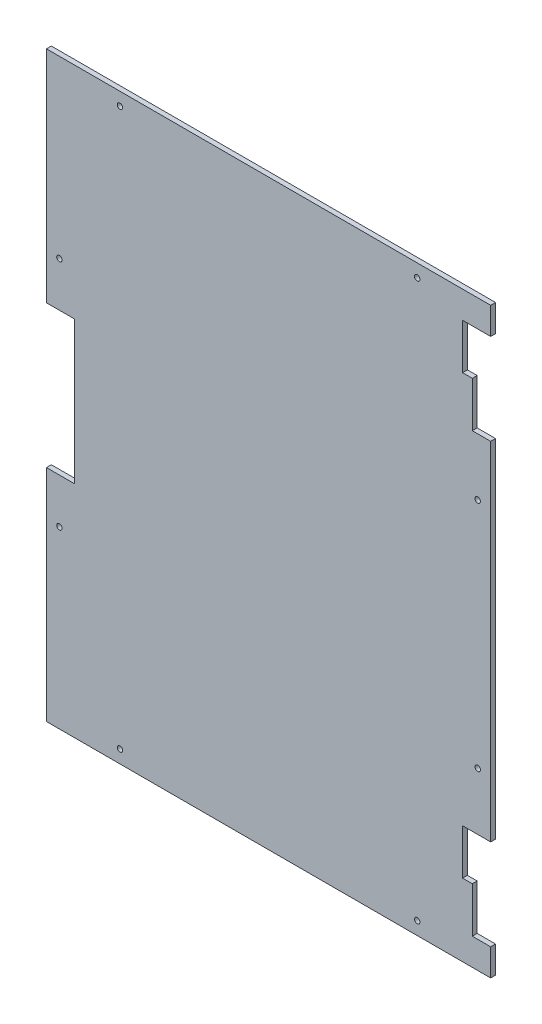
SolidWorks part; units mm, degrees
ref_plane "Front Plane" through (0, 0, 0) normal (0, 0, 1) x (1, 0, 0)
ref_plane "Top Plane" through (0, 0, 0) normal (0, 1, 0) x (1, 0, 0)
ref_plane "Right Plane" through (0, 0, 0) normal (1, 0, 0) x (0, 0, -1)
sketch "Sketch1" plane through (0, 0, 0) normal (0, 0, 1) x (1, 0, 0)
  line L11 (178.5, 202.5) -> (204.5, 202.5) construction
  line L16 (-206.5, 269.5) -> (204.5, 269.5)
  line L32 (-206.5, 269.5) -> (-206.5, 244.5)
  line L33 (-206.5, -269.5) -> (204.5, -269.5)
  line L35 (204.5, 244.5) -> (178.5, 244.5)
  line L37 (204.5, 160.5) -> (187.5, 160.5)
  line L39 (178.5, 202.5) -> (178.5, 244.5)
  line L40 (187.5, 202.5) -> (187.5, 160.5)
  line L41 (178.5, 202.5) -> (187.5, 202.5)
  line L42 (204.5, 160.5) -> (204.5, -160.5)
  line L43 (-206.5, 0) -> (204.5, 0) construction
  line L44 (204.5, -160.5) -> (178.5, -160.5)
  line L45 (178.5, -160.5) -> (178.5, -202.5)
  line L46 (178.5, -202.5) -> (187.5, -202.5)
  line L47 (187.5, -202.5) -> (187.5, -244.5)
  line L48 (187.5, -244.5) -> (204.5, -244.5)
  line L49 (204.5, 269.5) -> (204.5, 244.5)
  line L50 (204.5, -244.5) -> (204.5, -269.5)
  line L51 (-1, 269.5) -> (-1, -269.5) construction
  line L57 (-206.5, 160.5) -> (-206.5, 66)
  line L63 (-206.5, -244.5) -> (-206.5, -269.5)
  line L64 (-206.5, -66) -> (-206.5, -160.5)
  line L65 (-206.5, 66) -> (-180.5, 66)
  line L67 (-206.5, -66) -> (-180.5, -66)
  line L68 (-180.5, 66) -> (-180.5, -66)
  line L69 (-206.5, 244.5) -> (-206.5, 160.5)
  line L70 (-206.5, -160.5) -> (-206.5, -244.5)
  circle A0 centre (136.5, -257.5) radius 2.5
  circle A3 centre (-138.5, -257.5) radius 2.5
  circle A4 centre (-138.5, 257.5) radius 2.5
  circle A7 centre (136.5, 257.5) radius 2.5
  circle A8 centre (-194.5, 107.5) radius 2.5
  circle A9 centre (-194.5, -107.5) radius 2.5
  circle A10 centre (192.5, 107.5) radius 2.5
  circle A11 centre (192.5, -107.5) radius 2.5
  dimension "D5" = 25
  dimension "D3" = 206.5
  dimension "D7" = 17
  dimension "D10" = 26
  dimension "D11" = 84
  dimension "D6" = 26
  dimension "D8" = 84
  dimension "D18" = 12
  dimension "D21" = 12
  dimension "D1" = 539
  dimension "D2" = 411
  dimension "D4" = 269.5
  dimension "D9" = 42
  dimension "D12" = 42
  dimension "D13" = 17
  dimension "D14" = 25
  dimension "D15" = 26
  dimension "D16" = 132
  dimension "D17" = 66
  dimension "D19" = 68
  dimension "D20" = 12
  dimension "D22" = 12
  dimension "D23" = 12
  dimension "D24" = 12
extrude "Boss-Extrude1" add sketch "Sketch1" along normal blind 4.5
